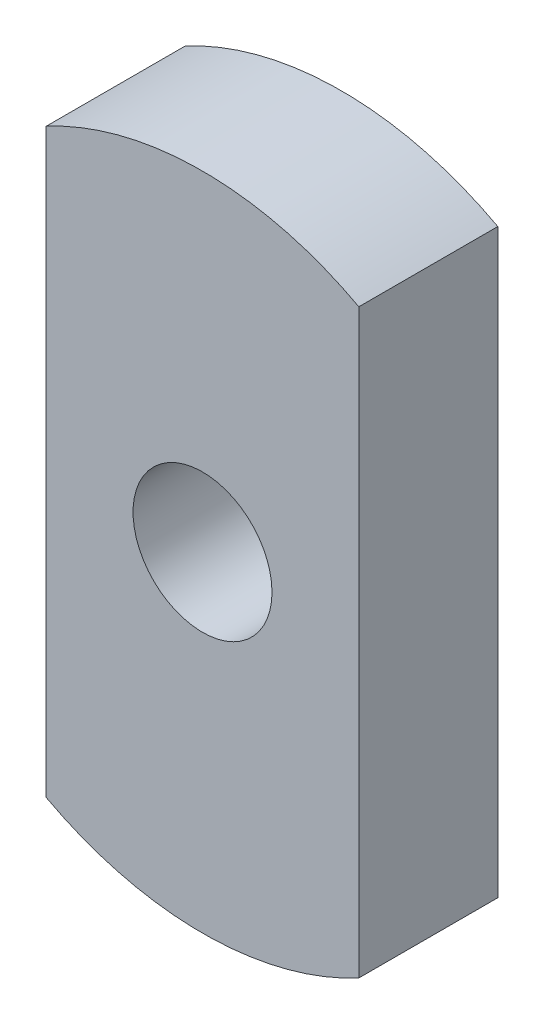
SolidWorks part; units mm, degrees
ref_plane "Front Plane" through (0, 0, 0) normal (0, 0, 1) x (1, 0, 0)
ref_plane "Top Plane" through (0, 0, 0) normal (0, 1, 0) x (1, 0, 0)
ref_plane "Right Plane" through (0, 0, 0) normal (1, 0, 0) x (0, 0, -1)
sketch "Sketch1" plane through (0, 0, 0) normal (0, 0, 1) x (1, 0, 0)
  line L0 (-4.5, 8.3666) -> (-4.5, -8.3666)
  line L1 (4.5, 8.3666) -> (4.5, -8.3666)
  circle A0 centre (0, 0) radius 9.5 construction
  circle A1 centre (0, 0) radius 2
  arc A2 (-4.5, 8.3666) -> (4.5, 8.3666) centre (0, 0) cw
  arc A3 (-4.5, -8.3666) -> (4.5, -8.3666) centre (0, 0) ccw
  dimension "D1" = 19
  dimension "D2" = 4
  dimension "D3" = 4.5
extrude "Boss-Extrude1" add sketch "Sketch1" along normal blind 4
